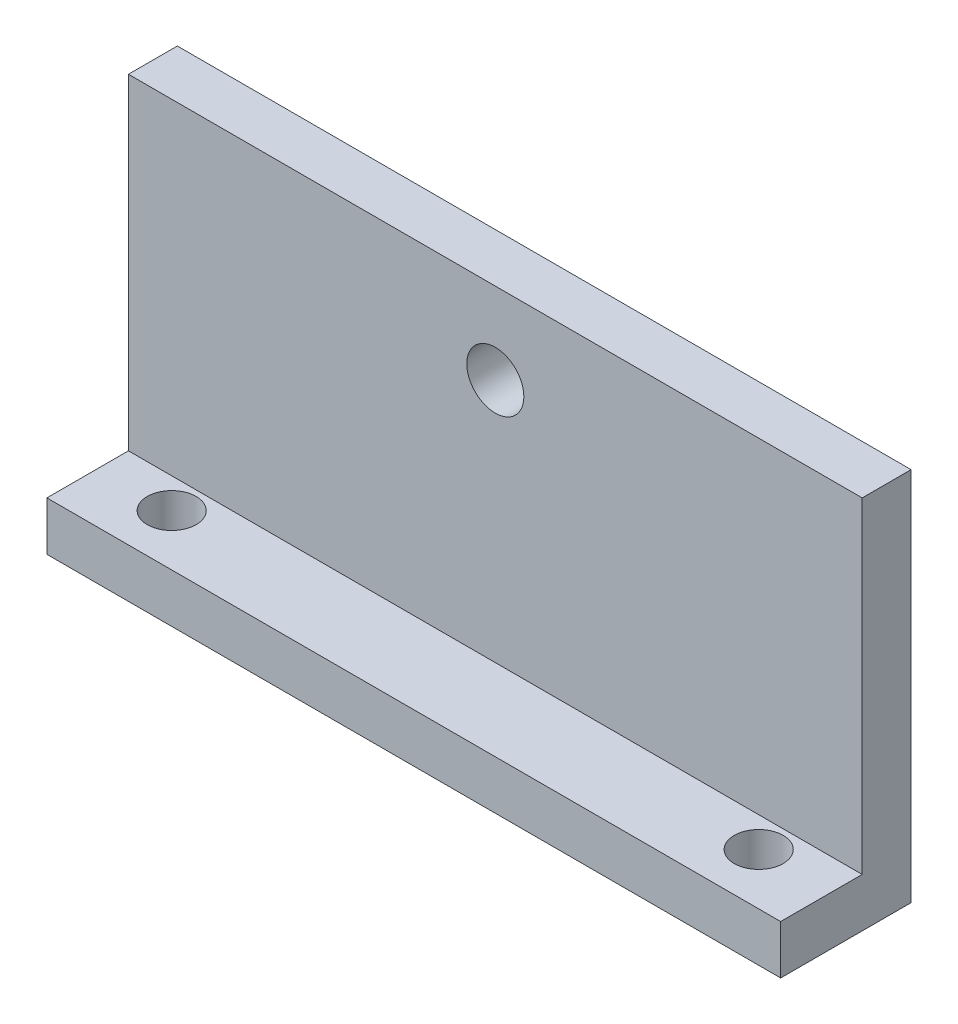
SolidWorks part; units mm, degrees
ref_plane "Plan de face" through (0, 0, 0) normal (0, 0, 1) x (1, 0, 0)
ref_plane "Plan de dessus" through (0, 0, 0) normal (0, 1, 0) x (1, 0, 0)
ref_plane "Plan de droite" through (0, 0, 0) normal (1, 0, 0) x (0, 0, -1)
sketch "Esquisse1" plane through (0, 0, 0) normal (0, 1, 0) x (1, 0, 0)
  line L0 (-16.4842, 0) -> (19.5158, 0) construction
  line L2 (-20.9842, -3.1533) -> (24.0158, -3.1533)
  line L3 (-20.9842, -3.1533) -> (-20.9842, 4.8467)
  line L4 (-20.9842, 4.8467) -> (24.0158, 4.8467)
  line L5 (24.0158, -3.1533) -> (24.0158, 4.8467)
  line L6 (-20.9842, -3.1533) -> (24.0158, 4.8467) construction
  line L7 (-20.9842, 4.8467) -> (24.0158, -3.1533) construction
  circle A0 centre (19.5158, 0) radius 1.5
  circle A1 centre (-16.4842, 0) radius 1.5
  point P5 (1.5158, 0.8467)
  point P10 (1.5158, 0)
  point P11 (0, 0)
  point P12 (1.5158, 1.2037)
  point P13 (1.5158, 0.8467)
  dimension "D2" = 3
  dimension "D3" = 3
  dimension "D1" = 36
  dimension "D4" = 45
  dimension "D5" = 8
extrude "Boss.-Extru.1" add sketch "Esquisse1" along normal blind 3
sketch "Esquisse2" plane through (0, 3, 0) normal (0, 1, 0) x (1, 0, 0)
  line L0 (-20.9842, 4.8467) -> (24.0158, 4.8467)
  line L1 (-20.9842, 4.8467) -> (-20.9842, 1.8467)
  line L2 (24.0158, 4.8467) -> (24.0158, 1.8467)
  line L3 (-20.9842, 1.8467) -> (24.0158, 1.8467)
  dimension "D1" = 3
extrude "Boss.-Extru.2" add sketch "Esquisse2" along normal blind 20
sketch "Esquisse3" plane through (0, 0, -1.8467) normal (0, 0, 1) x (1, 0, 0)
  line L0 (1.5158, 3) -> (1.5158, 18) construction
  line L1 (-20.9842, 3) -> (24.0158, 3) construction
  circle A0 centre (1.5158, 18) radius 1.75
  dimension "D2" = 3.5
  dimension "D1" = 15
extrude "Enlèv. mat.-Extru.1" cut sketch "Esquisse3" against normal blind 20
